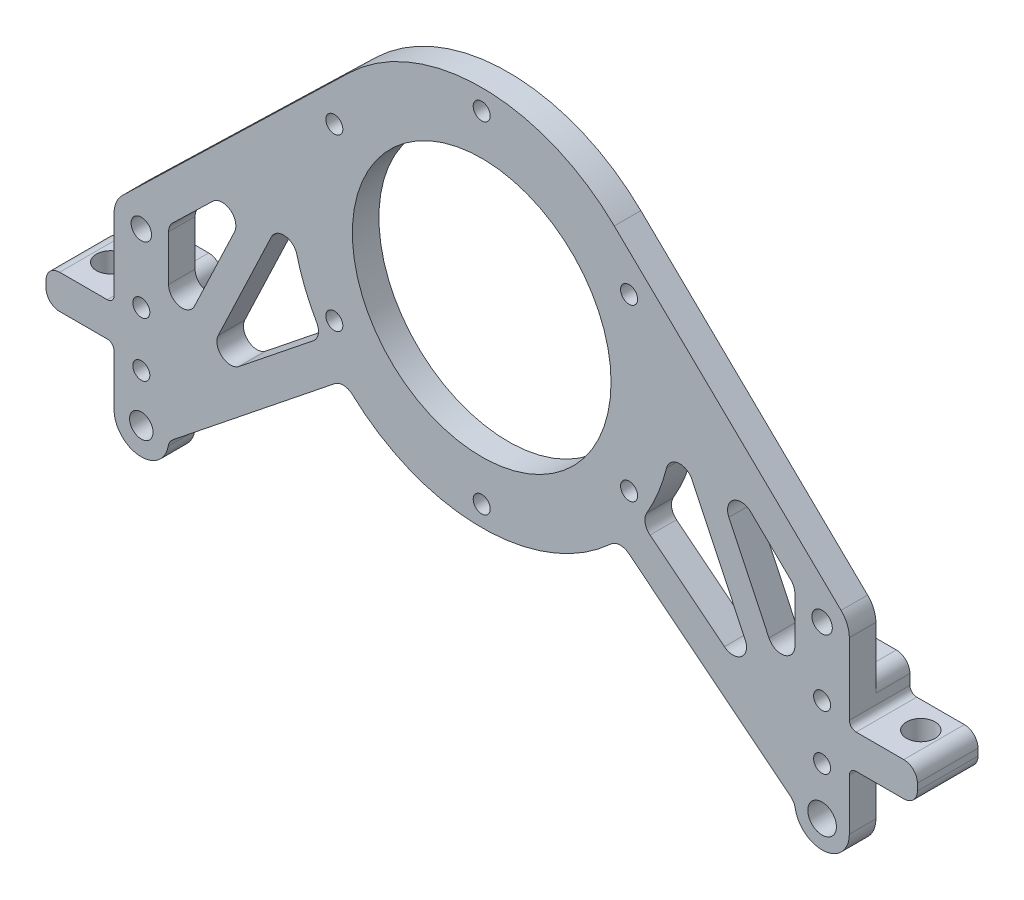
SolidWorks part; units mm, degrees
ref_plane "前视基准面" through (0, 0, 0) normal (0, 0, 1) x (1, 0, 0)
ref_plane "上视基准面" through (0, 0, 0) normal (0, 1, 0) x (1, 0, 0)
ref_plane "右视基准面" through (0, 0, 0) normal (1, 0, 0) x (0, 0, -1)
other "Configuration Table"
sketch "草图1" plane through (0, 0, 0) normal (0, 0, 1) x (1, 0, 0)
  circle A0 centre (0, 0) radius 28
  circle A1 centre (0, 0) radius 25 construction
  circle A2 centre (0, 0) radius 19
  circle A3 centre (0, 25) radius 1.25
  circle A4 centre (21.6506, 12.5) radius 1.25
  circle A5 centre (21.6506, -12.5) radius 1.25
  circle A6 centre (0, -25) radius 1.25
  circle A7 centre (-21.6506, -12.5) radius 1.25
  circle A8 centre (-21.6506, 12.5) radius 1.25
  point P19 (0, 0)
  dimension "D1" = 56
  dimension "D2" = 38
  dimension "D3" = 50
  dimension "D5" = 2.5
  dimension "D4" = 6
extrude "凸台-拉伸1" add sketch "草图1" along normal blind 3.9
sketch "草图2" plane through (0, 0, 0) normal (0, 0, -1) x (-1, 0, 0)
  line L0 (-46, -15) -> (-26.8264, -8.0214)
  line L1 (-50, -40) -> (-50, -15) construction
  line L2 (-54, -40) -> (-54, -15)
  line L3 (-46, -40) -> (-46, -15)
  line L4 (-19.4753, 20.1175) -> (-52.7822, -12.1261)
  line L5 (0, 0) -> (0, -40) construction
  line L6 (19.4753, 20.1175) -> (52.7822, -12.1261)
  line L7 (46, -15) -> (26.8264, -8.0214)
  line L8 (50, -40) -> (50, -15) construction
  line L9 (54, -40) -> (54, -15)
  line L10 (46, -40) -> (46, -15)
  line L11 (0, 0) -> (-50, -40) construction
  line L12 (1.5617, -1.9522) -> (-48.4383, -41.9522)
  line L13 (-1.5617, 1.9522) -> (-51.5617, -38.0478)
  line L14 (0, 0) -> (50, -40) construction
  line L15 (1.5617, 1.9522) -> (51.5617, -38.0478)
  line L16 (-1.5617, -1.9522) -> (48.4383, -41.9522)
  arc A0 (54, -40) -> (46, -40) centre (50, -40) cw
  arc A1 (-54, -40) -> (-46, -40) centre (-50, -40) ccw
  arc A2 (-46, -15) -> (-54, -15) centre (-50, -15) ccw
  circle A3 centre (0, 0) radius 28 construction
  arc A4 (46, -15) -> (54, -15) centre (50, -15) cw
  circle A5 centre (-50, -40) radius 2.1
  circle A6 centre (50, -40) radius 1.7265
  arc A7 (1.5617, -1.9522) -> (-1.5617, 1.9522) centre (0, 0) ccw
  arc A8 (-51.5617, -38.0478) -> (-48.4383, -41.9522) centre (-50, -40) ccw
  arc A9 (1.5617, 1.9522) -> (-1.5617, -1.9522) centre (0, 0) ccw
  arc A10 (48.4383, -41.9522) -> (51.5617, -38.0478) centre (50, -40) ccw
  circle A11 centre (0, 0) radius 28
  point P6 (-50, -27.5)
  point P22 (50, -27.5)
  point P30 (-25, -20)
  point P36 (25, -20)
  circle M6 centre (0, 0) radius 28
  dimension "D2" = 4
  dimension "D6" = 2.5
  dimension "D7" = 2.5
  dimension "D1" = 25
  dimension "D3" = 50
  dimension "D4" = 40
  dimension "D5" = 110
extrude "凸台-拉伸2" add sketch "草图2" against normal blind 3.9 contours A2 L0 L4 M6 | A8 L13 L3 A2 L2 A1 L12 | A1 L12 L13 L3 M6 | L13 A8 L12 A1 L3 A5 | L16 A0 L10 L15 M6 | A10 L16 A0 L9 A4 L10 L15 | L7 A4 L6 M6 | L16 A10 L15 L10 A0 A6 | L13 L0 L3 M6 | L15 L10 L7 M6
sketch "草图4" plane through (0, 0, 0) normal (0, 0, -1) x (-1, 0, 0)
  line L3 (-15.9975, 16.5251) -> (-49.3045, -15.7185)
  line L4 (-27.4708, 5.4181) -> (-46, -12.5195)
  line L6 (-46, -40) -> (-46, -15)
  line L7 (-46, -33.5984) -> (-46, -12.5195)
  line L9 (-23.3387, -15.4694) -> (-49.1235, -36.0972)
  line L10 (-23.3387, -15.4694) -> (-46, -33.5984)
  line L12 (23.3387, -15.4694) -> (49.1235, -36.0972)
  line L13 (23.3387, -15.4694) -> (46, -33.5984)
  line L15 (15.9975, 16.5251) -> (49.3045, -15.7185)
  line L16 (27.4708, 5.4181) -> (46, -12.5195)
  line L18 (46, -40) -> (46, -15)
  line L19 (46, -33.5984) -> (46, -12.5195)
  circle A0 centre (0, 0) radius 28
  dimension "D1" = 5
  dimension "D2" = 8
  dimension "D3" = 5
  dimension "D4" = 5
  dimension "D5" = 5
  dimension "D6" = 8
extrude "切除-拉伸2" cut sketch "草图4" against normal blind 3.9 contours A0 L4 L7 L10 | A0 L13 L19 L16
sketch "草图5" plane through (0, 0, 0) normal (0, 0, -1) x (-1, 0, 0)
  line L0 (-46, -33.5984) -> (-27.4708, 5.4181) construction
  line L1 (-47.8066, -32.7405) -> (-29.2774, 6.2761)
  line L2 (-44.1934, -34.4564) -> (-25.6642, 4.5602)
  line L3 (27.4708, 5.4181) -> (46, -33.5984) construction
  line L4 (29.2774, 6.2761) -> (47.8066, -32.7405)
  line L5 (25.6642, 4.5602) -> (44.1934, -34.4564)
  line L6 (27.4708, 5.4181) -> (46, -12.5195) construction
  line L7 (46, -33.5984) -> (46, -12.5195) construction
  arc A0 (-47.8066, -32.7405) -> (-44.1934, -34.4564) centre (-46, -33.5984) ccw
  arc A1 (-25.6642, 4.5602) -> (-29.2774, 6.2761) centre (-27.4708, 5.4181) ccw
  arc A6 (29.2774, 6.2761) -> (25.6642, 4.5602) centre (27.4708, 5.4181) ccw
  arc A7 (44.1934, -34.4564) -> (47.8066, -32.7405) centre (46, -33.5984) ccw
  arc A8 (23.3387, -15.4694) -> (27.4708, 5.4181) centre (0, 0) ccw construction
  point P3 (-36.7354, -14.0901)
  point P8 (36.7354, -14.0901)
  dimension "D1" = 2
  dimension "D2" = 2
extrude "凸台-拉伸4" add sketch "草图5" against normal blind 3.9
sketch "草图7" plane through (0, 0, 3.9) normal (0, 0, 1) x (1, 0, 0)
  line L0 (-46, -28.9363) -> (-46, -12.5195) construction
  line L1 (0, 0) -> (0, -9.4221) construction
  circle A0 centre (-50, -15) radius 1.5
  circle A1 centre (-50, -33) radius 1.25
  circle A2 centre (-50, -25) radius 1.25
  circle A3 centre (-50, -40) radius 1.7265 construction
  circle A4 centre (50, -15) radius 1.5
  circle A5 centre (50, -25) radius 1.25
  circle A6 centre (50, -33) radius 1.25
  dimension "D1" = 50
  dimension "D3" = 3
  dimension "D4" = 7
  dimension "D5" = 8
  dimension "D6" = 2.5
  dimension "D7" = 4
  dimension "D8" = 2.5
  dimension "D2" = 15
fillet "圆角4" radius 2 16 edges at (46, -40.0016, 1.95) (20.2153, -19.3738, 1.95) (-20.2153, -19.3738, 1.95) (-46, -40.0016, 1.95) (23.3387, -15.4694, 1.95) (42.4293, -30.7419, 1.95) (27.9978, -0.3537, 1.95) (31.569, 1.4508, 1.95) (46, -28.9363, 1.95) (-23.3387, -15.4694, 1.95) (-27.9978, -0.3537, 1.95) (-42.4293, -30.7419, 1.95) (-46, -12.5195, 1.95) (-46, -28.9363, 1.95) (-31.569, 1.4508, 1.95) (46, -12.5195, 1.95)
extrude "切除-拉伸4" cut sketch "草图7" against normal blind 3.9
sketch "草图8" plane through (0, 0, 3.9) normal (0, 0, 1) x (1, 0, 0)
  line L0 (54, -40) -> (54, -15) construction
  line L1 (47, -22) -> (54, -22)
  line L2 (47, -22) -> (47, -36)
  line L3 (47, -36) -> (54, -36)
  line L4 (54, -22) -> (54, -36)
  line L5 (47, -22) -> (54, -36) construction
  line L6 (47, -36) -> (54, -22) construction
  line L7 (0, 0) -> (0, -37.1756) construction
  line L8 (64, -31.5) -> (54, -31.5)
  line L9 (64, -31.5) -> (64, -26.5)
  line L10 (64, -26.5) -> (54, -26.5)
  line L11 (54, -31.5) -> (54, -26.5)
  line L12 (64, -31.5) -> (54, -26.5) construction
  line L13 (64, -26.5) -> (54, -31.5) construction
  line L14 (-64, -26.5) -> (-54, -31.5) construction
  line L15 (-64, -31.5) -> (-54, -26.5) construction
  line L16 (-47, -36) -> (-54, -22) construction
  line L17 (-47, -22) -> (-54, -36) construction
  line L18 (-54, -31.5) -> (-54, -26.5)
  line L19 (-64, -26.5) -> (-54, -26.5)
  line L20 (-64, -31.5) -> (-64, -26.5)
  line L21 (-64, -31.5) -> (-54, -31.5)
  line L22 (-54, -22) -> (-54, -36)
  line L23 (-47, -36) -> (-54, -36)
  line L24 (-47, -22) -> (-47, -36)
  line L25 (-47, -22) -> (-54, -22)
  circle A0 centre (50, -25) radius 1.25 construction
  circle A1 centre (50, -33) radius 1.25 construction
  circle A2 centre (50, -25) radius 1.5
  circle A3 centre (50, -33) radius 1.5
  circle A4 centre (-50, -33) radius 1.5
  circle A5 centre (-50, -25) radius 1.5
  point P0 (50.5, -29)
  point P11 (59, -29)
  point P37 (-59, -29)
  point P38 (-50.5, -29)
  dimension "D1" = 3
  dimension "D2" = 3
  dimension "D3" = 3
  dimension "D6" = 3
  dimension "D7" = 3
  dimension "D4" = 5
  dimension "D5" = 10
extrude "凸台-拉伸5" add sketch "草图8" against normal blind 5 from surface at -3.9 contours L4 L1 L2 L3 A3 A2 | L9 L10 L4 L8 | L24 L25 L22 L18 L23 A4 A5 | L20 L21 L18 L19 starting at face at (-48.75, -33, 0)
sketch "草图9" plane through (0, 0, -5) normal (0, 0, -1) x (-1, 0, 0)
  line L0 (-64, -26.5) -> (-64, -31.5)
  line L1 (-64, -26.5) -> (-54, -26.5)
  line L2 (-64, -31.5) -> (-54, -31.5)
  line L3 (-54, -26.5) -> (-54, -31.5)
  line L6 (-54, -31.5) -> (-54, -36) construction
  line L11 (54, -26.5) -> (54, -31.5)
  line L12 (64, -26.5) -> (54, -26.5)
  line L13 (64, -31.5) -> (64, -26.5)
  line L14 (54, -31.5) -> (64, -31.5)
  line L15 (54, -26.5) -> (54, -31.5)
  line L16 (64, -26.5) -> (54, -26.5)
  line L17 (64, -31.5) -> (64, -26.5)
  line L18 (54, -31.5) -> (64, -31.5)
  dimension "D1" = 0
extrude "凸台-拉伸6" add sketch "草图9" against normal blind 3.9 from surface at -5 starting at face at (-48.75, -33, 0)
sketch "草图10" plane through (0, -31.5, 0) normal (0, -1, 0) x (1, 0, 0)
  line L0 (64, -5) -> (64, 3.9) construction
  line L1 (64, -5) -> (54, -5) construction
  circle A0 centre (59.5, -1.1) radius 2.1
  dimension "D1" = 4.2
  dimension "D2" = 4.5
  dimension "D3" = 3.9
extrude "切除-拉伸5" cut sketch "草图10" against normal blind 5
fillet "圆角5" radius 2 12 edges at (54, -36, -2.5) (47, -36, -2.5) (47, -22, -2.5) (54, -22, -2.5) (64, -26.5, -0.55) (64, -31.5, -0.55) (-54, -36, -2.5) (-64, -31.5, -0.55) (-64, -26.5, -0.55) (-54, -22, -2.5) (-47, -22, -2.5) (-47, -36, -2.5)
fillet "圆角6" radius 1 4 edges at (54, -31.5, -0.55) (54, -26.5, -0.55) (-54, -31.5, -0.55) (-54, -26.5, -0.55)
mirror "镜向9" about plane through (0, 0, 0) normal (1, 0, 0) of "切除-拉伸5"
sketch "草图12" plane through (0, 0, 0) normal (0, 0, -1) x (-1, 0, 0)
  line L0 (-54, 0) -> (54, 0) construction
  line L1 (54, -12.5) -> (54, 12.5)
  line L2 (54, 12.5) -> (10.46, 28.4871)
  line L3 (54, -12.5) -> (10.46, -28.4871)
  line L4 (0, 0) -> (0, -6.7174) construction
  line L5 (-54, -12.5) -> (-10.46, -28.4871)
  line L6 (-54, 12.5) -> (-10.46, 28.4871)
  line L7 (-54, -12.5) -> (-54, 12.5)
  line L8 (-54, -12.5) -> (-20, -50)
  line L9 (-20, -50) -> (0, -50)
  line L10 (0, 0) -> (0, -50) construction
  line L11 (20, -50) -> (0, -50)
  line L12 (54, -12.5) -> (20, -50)
  circle A0 centre (0, 0) radius 30.3468
  circle A1 centre (0, 0) radius 19
  circle A2 centre (21.6506, 12.5) radius 1.25 construction
  circle A3 centre (21.6506, -12.5) radius 1.25 construction
  circle A4 centre (0, -25) radius 1.25 construction
  circle A5 centre (-21.6506, -12.5) radius 1.25 construction
  circle A6 centre (-21.6506, 12.5) radius 1.25 construction
  circle A7 centre (0, 25) radius 1.25 construction
  circle A8 centre (21.6506, 12.5) radius 1.25
  circle A9 centre (21.6506, -12.5) radius 1.25
  circle A10 centre (0, -25) radius 1.25
  circle A11 centre (-21.6506, -12.5) radius 1.25
  circle A12 centre (-21.6506, 12.5) radius 1.25
  circle A13 centre (0, 25) radius 1.25
  circle A14 centre (48.2144, 9) radius 2.15
  circle A15 centre (48.2144, -9) radius 2.15
  circle A16 centre (-48.2144, -9) radius 2.15
  circle A17 centre (-48.2144, 9) radius 2.15
  circle A18 centre (0, 0) radius 40 construction
  circle A19 centre (-15, -43.3978) radius 2.15
  circle A20 centre (15, -43.3978) radius 2.15
  dimension "D2" = 4.3
  dimension "D3" = 9
  dimension "D4" = 20
  dimension "D6" = 15
  dimension "D1" = 25
  dimension "D5" = 50
